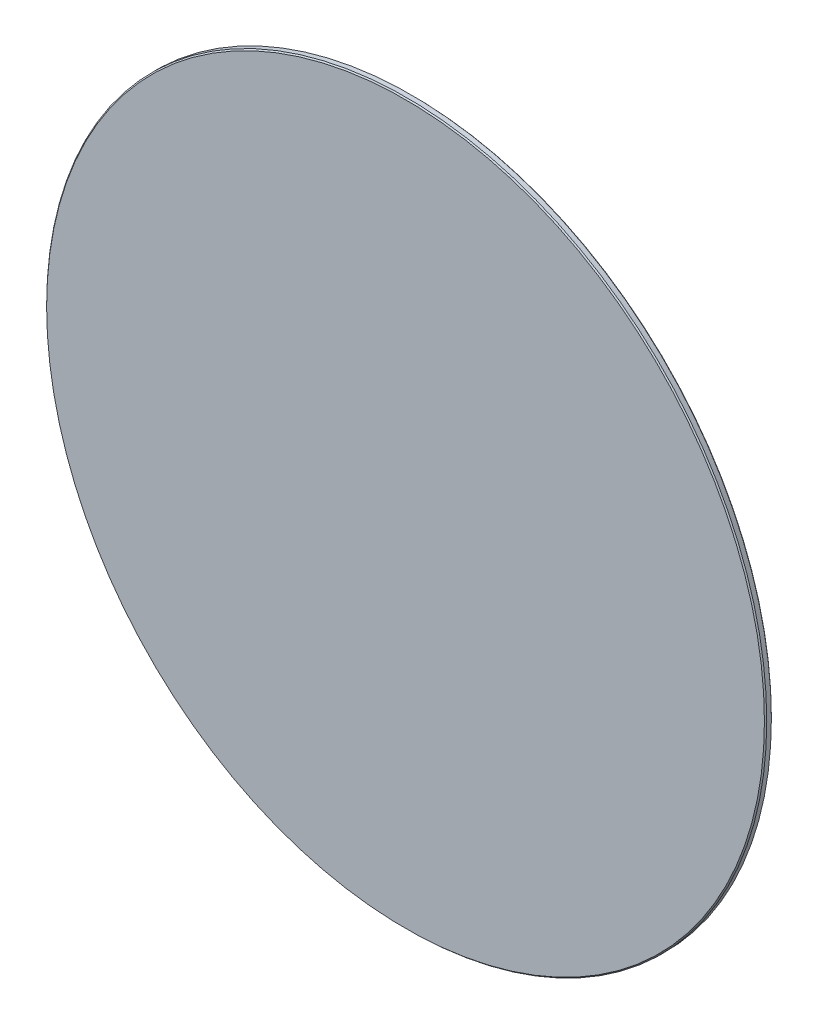
SolidWorks part; units mm, degrees
ref_plane "Front Plane" through (0, 0, 0) normal (0, 0, 1) x (1, 0, 0)
ref_plane "Top Plane" through (0, 0, 0) normal (0, 1, 0) x (1, 0, 0)
ref_plane "Right Plane" through (0, 0, 0) normal (1, 0, 0) x (0, 0, -1)
sketch "Sketch1" plane through (0, 0, 0) normal (0, 0, 1) x (1, 0, 0)
  circle A0 centre (0, 0) radius 155
  dimension "D1" = 310
extrude "Boss-Extrude1" add sketch "Sketch1" along normal blind 3
chamfer "Chamfer1" distance 0.5 angle 45 2 edges at (155, 0, 0) (155, 0, 3)
sketch "Sketch2" plane through (0, 0, 3) normal (0, 0, 1) x (1, 0, 0)
  circle A0 centre (0, 0) radius 139.7 construction
  dimension "D1" = 279.4
